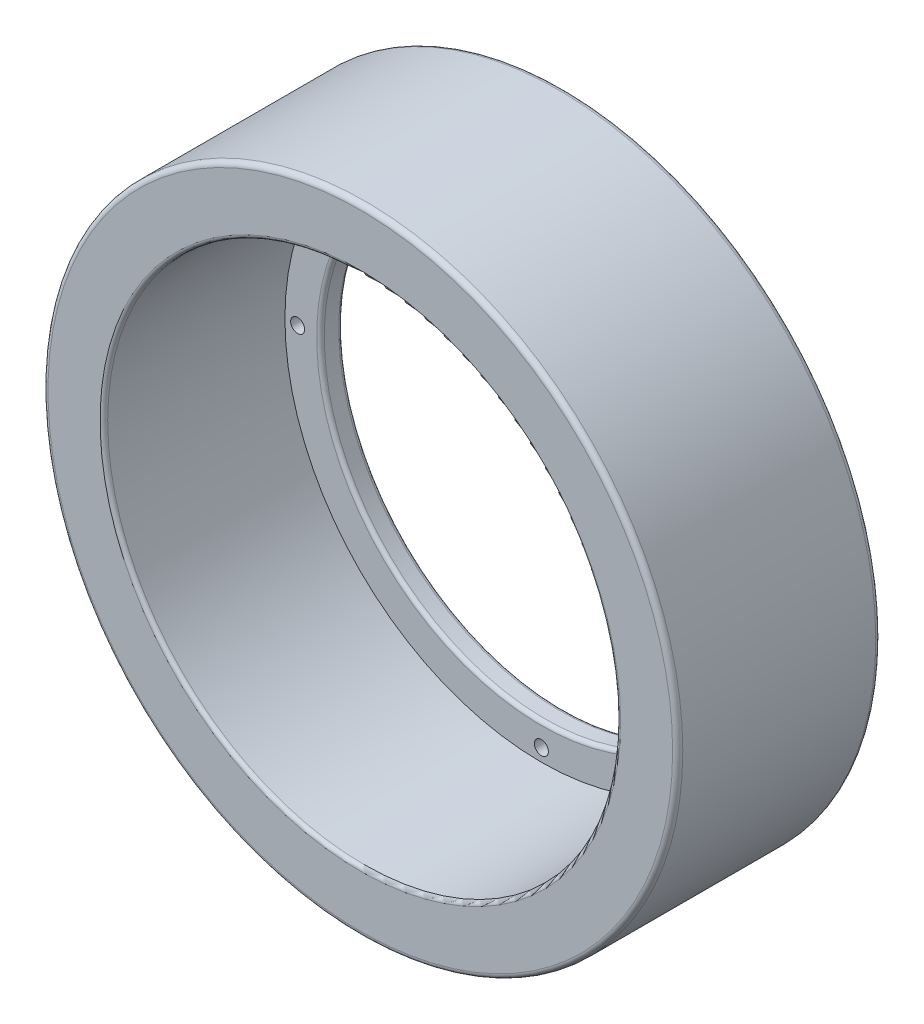
SolidWorks part; units mm, degrees
material "Gomma"
ref_plane "Piano frontale" through (0, 0, 0) normal (0, 0, 1) x (1, 0, 0)
ref_plane "Piano superiore" through (0, 0, 0) normal (0, 1, 0) x (1, 0, 0)
ref_plane "Piano destro" through (0, 0, 0) normal (1, 0, 0) x (0, 0, -1)
sketch "Schizzo1" plane through (0, 0, 0) normal (0, 0, 1) x (1, 0, 0)
  circle A0 centre (0, 0) radius 125
  circle A1 centre (0, 0) radius 101
  dimension "D1" = 250
  dimension "D2" = 202
extrude "Estrusione-Estrusione1" add sketch "Schizzo1" along normal blind 80
fillet "Raccordo1" radius 2 2 edges at (125, 0, 0) (125, 0, 80)
sketch "Schizzo3" plane through (0, 0, 0) normal (0, 0, 1) x (1, 0, 0)
  circle A0 centre (0, 0) radius 87
  circle A1 centre (0, 0) radius 101 construction
  circle A2 centre (0, 0) radius 101
  dimension "D1" = 174
extrude "Estrusione-Estrusione2" add sketch "Schizzo3" along normal blind 8.7
fillet "Raccordo2" radius 1.5 3 edges at (87, 0, 0) (87, 0, 8.7) (101, 0, 80)
sketch "Schizzo6" plane through (0, 0, 0) normal (0, 0, -1) x (-1, 0, 0)
  line L0 (0, -1000) -> (0, 49000) construction
  line L1 (-1000, 0) -> (49000, 0) construction
  point P8 (96, 0)
  point P9 (0, -96)
  point P10 (-96, 0)
  point P11 (0, 96)
  dimension "D1" = 4
  dimension "D2" = 96
  dimension "D3" = 96
  dimension "D4" = 96
hole_wizard "Foro lamato per Bullone M5 a testa esagonale-1" positions "Schizzo3D4" profile "Schizzo9" counterbore size "M5" standard "Ansi Metric" end condition through all
sketch3d "Schizzo3D4"
  point P0 (0, 96, 0)
  point P3 (-96, 0, 0)
  point P6 (0, -96, 0)
  point P9 (96, 0, 0)
sketch "Schizzo9" plane through (0, 96, 0) normal (1, 0, 0) x (0, 1, 0)
  line L0 (0, 0) -> (0, 80)
  line L1 (0, 80) -> (2.75, 80)
  line L3 (2.75, 80) -> (2.75, 3.58)
  line L4 (6.12, 3.58) -> (2.75, 3.58)
  line L5 (6.12, 3.58) -> (6.12, 0.025)
  line L6 (6.12, 0.025) -> (6.145, 0)
  line L7 (6.145, 0) -> (0, 0)
  line L8 (-6.12, 0.025) -> (-6.145, 0) construction
  line L11 (0, -6.35) -> (0, 107.95) construction
  dimension "Thru Hole Dia." = 5.5
  dimension "Thru Hole Depth" = 80
  dimension "C'Bore Dia." = 12.24
  dimension "C'Bore Depth" = 3.58
  dimension "Near C'Sink Dia." = 12.29
  dimension "Near C'Sink Angle" = 90
ref_plane "Piano2" through (0, -125, 0) normal (0, -1, 0) x (-1, 0, 0)
ref_plane "Piano3" through (0, 0, 40) normal (0, 0, 1) x (1, 0, 0)
sketch "Schizzo13" plane through (0, 0, 40) normal (0, 0, 1) x (1, 0, 0)
  line L0 (0, -1000) -> (0, 49000) construction
